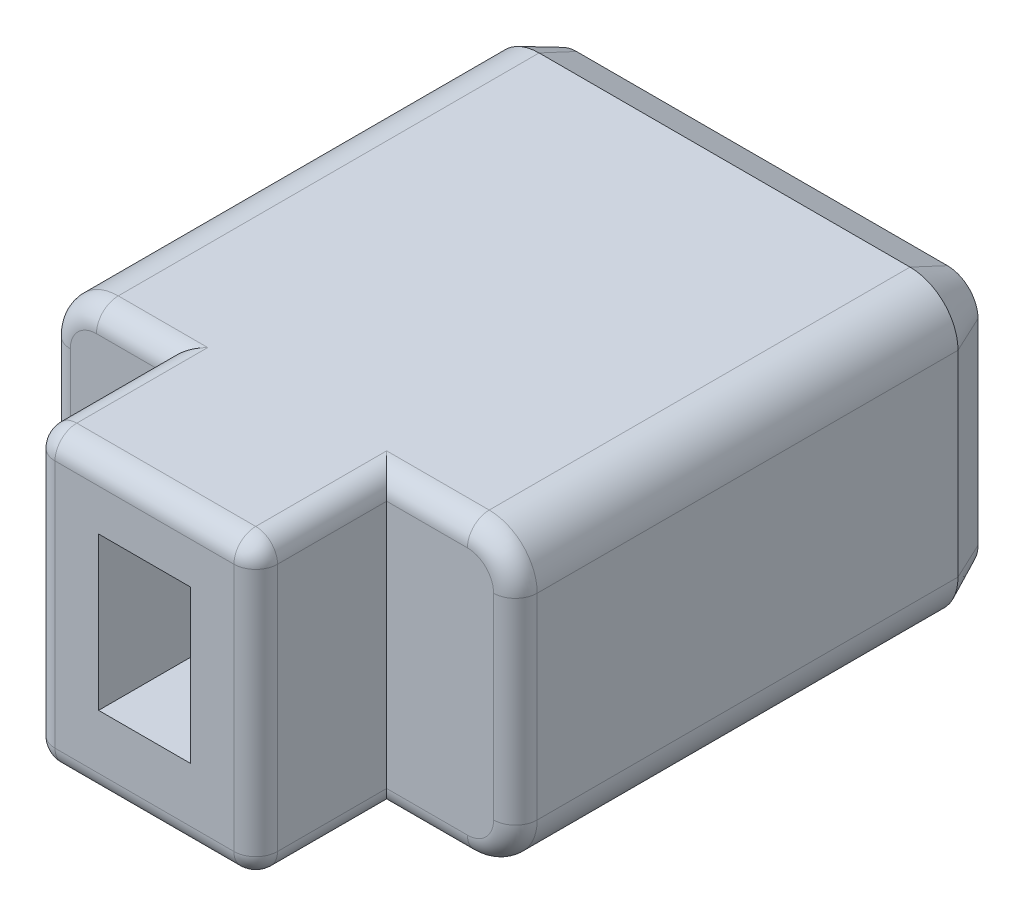
SolidWorks part; units mm, degrees
ref_plane "Plan de face" through (0, 0, 0) normal (0, 0, 1) x (1, 0, 0)
ref_plane "Plan de dessus" through (0, 0, 0) normal (0, 1, 0) x (1, 0, 0)
ref_plane "Plan de droite" through (0, 0, 0) normal (1, 0, 0) x (0, 0, -1)
sketch "Esquisse2" plane through (0, 0, 0) normal (0, 0, 1) x (1, 0, 0)
  line L1 (1.1, 0) -> (9.6, 0)
  line L2 (0, 1.1) -> (0, 5.6)
  line L3 (1.1, 6.7) -> (9.6, 6.7)
  line L4 (10.7, 1.1) -> (10.7, 5.6)
  arc A0 (9.6, 6.7) -> (10.7, 5.6) centre (9.6, 5.6) cw
  arc A1 (9.6, 0) -> (10.7, 1.1) centre (9.6, 1.1) ccw
  arc A2 (1.1, 0) -> (0, 1.1) centre (1.1, 1.1) cw
  arc A3 (0, 5.6) -> (1.1, 6.7) centre (1.1, 5.6) cw
  point P7 (10.7, 6.7)
  point P12 (0, 0)
  point P15 (0, 6.7)
  dimension "D3" = 1.1
  dimension "D1" = 10.7
  dimension "D2" = 6.7
extrude "Boss.-Extru.1" add sketch "Esquisse2" along normal blind 14
sketch "Esquisse3" plane through (0, 0, 14) normal (0, 0, 1) x (1, 0, 0)
  line L0 (0, 5.6) -> (0, 1.1) construction
  line L1 (4.15, 5.25) -> (6.25, 5.25)
  line L2 (4.15, 5.25) -> (4.15, 1.75)
  line L3 (4.15, 1.75) -> (6.25, 1.75)
  line L4 (6.25, 5.25) -> (6.25, 1.75)
  line L5 (10.7, 1.1) -> (10.7, 5.6) construction
  line L6 (9.6, 6.7) -> (1.1, 6.7) construction
  line L7 (1.1, 0) -> (9.6, 0) construction
  dimension "D1" = 2.1
  dimension "D2" = 3.5
  dimension "D3" = 4.15
  dimension "D4" = 4.45
  dimension "D5" = 1.45
  dimension "D6" = 1.75
extrude "Enlèv. mat.-Extru.1" cut sketch "Esquisse3" against normal blind 3
sketch "Esquisse4" plane through (0, 0, 14) normal (0, 0, 1) x (1, 0, 0)
  line L0 (2.65, 6.7) -> (2.65, 0)
  line L1 (9.6, 6.7) -> (1.1, 6.7) construction
  line L2 (1.1, 0) -> (9.6, 0) construction
  line L3 (2.65, 0) -> (7.75, 0)
  line L4 (7.75, 0) -> (7.75, 6.7)
  line L5 (7.75, 6.7) -> (2.65, 6.7)
  line L6 (4.15, 5.25) -> (4.15, 1.75) construction
  line L7 (6.25, 1.75) -> (6.25, 5.25) construction
  dimension "D1" = 1.5
  dimension "D2" = 1.5
extrude "Enlèv. mat.-Extru.2" cut sketch "Esquisse4" against normal blind 3 flip side to cut
fillet "Congé1" radius 0.5 18 edges at (8.675, 0, 11) (10.3778, 0.3222, 11) (10.7, 3.35, 11) (10.3778, 6.3778, 11) (1.875, 6.7, 11) (0.3222, 6.3778, 11) (1.875, 0, 11) (0.3222, 0.3222, 11) (7.75, 6.7, 12.5) (2.65, 6.7, 12.5) (7.75, 0, 12.5) (2.65, 0, 12.5) (2.65, 3.35, 14) (5.2, 6.7, 14) (7.75, 3.35, 14) (5.2, 0, 14) (8.675, 6.7, 11) (0, 3.35, 11)
chamfer "Chanfrein1" distance 0.4 angle 65 8 edges at (5.35, 0, 0) (10.3778, 0.3222, 0) (0.3222, 0.3222, 0) (10.7, 3.35, 0) (0, 3.35, 0) (10.3778, 6.3778, 0) (0.3222, 6.3778, 0) (5.35, 6.7, 0)
